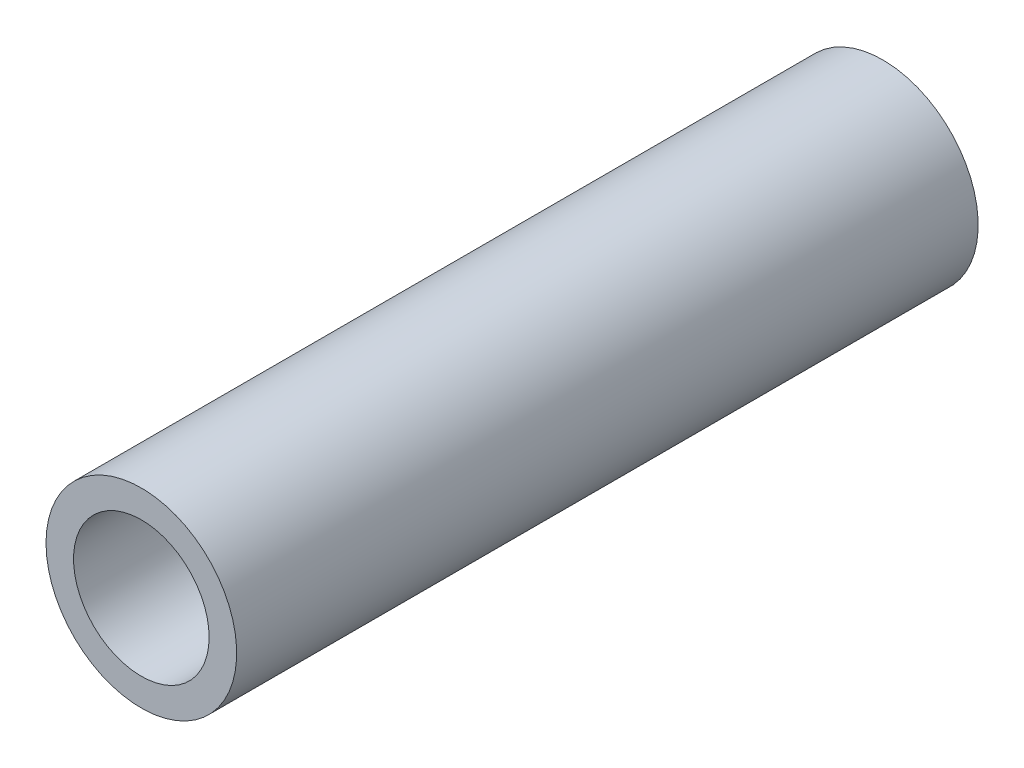
SolidWorks part; units mm, degrees
ref_plane "Front Plane" through (0, 0, 0) normal (0, 0, 1) x (1, 0, 0)
ref_plane "Top Plane" through (0, 0, 0) normal (0, 1, 0) x (1, 0, 0)
ref_plane "Right Plane" through (0, 0, 0) normal (1, 0, 0) x (0, 0, -1)
sketch "Sketch2" plane through (0, 0, 0) normal (0, 0, 1) x (1, 0, 0)
  circle A1 centre (0, 0) radius 5.715
  dimension "D2" = 11.43
extrude "Boss-Extrude1" add sketch "Sketch2" along normal blind 19.05 contours A1
sketch "Sketch3" plane through (0, 0, 0) normal (0, 0, -1) x (-1, 0, 0)
  line L2 (-1.7107, 2.4765) -> (1.7107, 2.4765)
  arc A1 (-1.7107, 2.4765) -> (1.7107, 2.4765) centre (0, 0) ccw
  dimension "D1" = 6.0198
  dimension "D2" = 3.4214
extrude "Cut-Extrude1" cut sketch "Sketch3" against normal through all
sketch "Sketch9" plane through (0, 0, 19.05) normal (0, 0, 1) x (1, 0, 0)
  circle A0 centre (0, 0) radius 5.715
  dimension "D1" = 11.43
extrude "Boss-Extrude5" add sketch "Sketch9" along normal blind 12.7
sketch "Sketch10" plane through (0, 0, 31.75) normal (0, 0, 1) x (1, 0, 0)
  circle A0 centre (0, 0) radius 5.715
  dimension "D1" = 11.43
extrude "Boss-Extrude6" add sketch "Sketch10" along normal blind 12.7
sketch "Sketch11" plane through (0, 0, 44.45) normal (0, 0, 1) x (1, 0, 0)
  circle A0 centre (0, 0) radius 4.064
  dimension "D1" = 8.128
extrude "Cut-Extrude2" cut sketch "Sketch11" against normal blind 19.05
